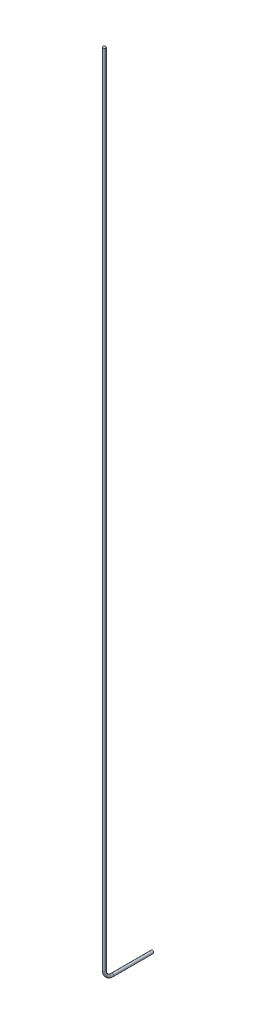
SolidWorks part; units mm, degrees
ref_plane "正面" through (0, 0, 0) normal (0, 0, 1) x (1, 0, 0)
ref_plane "平面" through (0, 0, 0) normal (0, 1, 0) x (1, 0, 0)
ref_plane "右側面" through (0, 0, 0) normal (1, 0, 0) x (0, 0, -1)
sketch "ｽｹｯﾁ1" plane through (0, 0, 0) normal (0, 0, 1) x (1, 0, 0)
  circle A0 centre (0, 0) radius 0.9
  dimension "D1" = 1.8
extrude "ﾎﾞｽ - 押し出し1" add sketch "ｽｹｯﾁ1" along normal blind 20
sketch "ｽｹｯﾁ2" plane through (0, 0, 20) normal (0, 0, 1) x (1, 0, 0)
  circle A1 centre (0, 0) radius 0.9
  circle A2 centre (0, 0) radius 0.9
  dimension "D1" = 0
sketch "ｽｹｯﾁ3" plane through (0, 0, 0) normal (1, 0, 0) x (0, 0, -1)
  line L0 (-20, 0) -> (-25, 0)
  line L1 (-20, 0.9) -> (-20, -0.9) construction
  line L2 (-30, 5) -> (-30, 505)
  line L3 (-20, 0.9) -> (-20, -0.9) construction
  arc A0 (-25, 0) -> (-30, 5) centre (-25, 5) cw
  point P8 (-30, 0)
  dimension "D2" = 5
  dimension "D1" = 10
  dimension "D3" = 500
sweep "ｽｲｰﾌﾟ1" add profiles "ｽｹｯﾁ2" path "ｽｹｯﾁ3"
